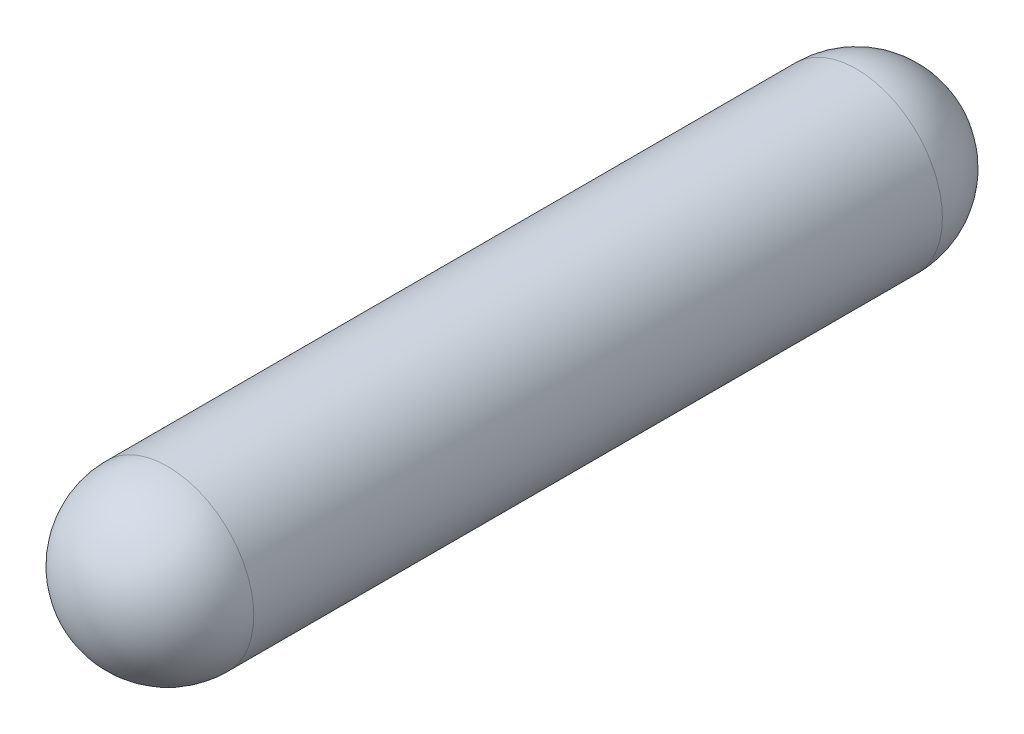
SolidWorks part; units mm, degrees
ref_plane "Front Plane" through (0, 0, 0) normal (0, 0, 1) x (1, 0, 0)
ref_plane "Top Plane" through (0, 0, 0) normal (0, 1, 0) x (1, 0, 0)
ref_plane "Right Plane" through (0, 0, 0) normal (1, 0, 0) x (0, 0, -1)
sketch "Sketch10" plane through (0, 0, 0) normal (0, 1, 0) x (1, 0, 0)
  line L0 (0, 0) -> (0, 10000)
  line L1 (1000, 1000) -> (1000, 9000)
  arc A0 (0, 0) -> (1000, 1000) centre (0, 1000) ccw
  arc A1 (0, 10000) -> (1000, 9000) centre (0, 9000) cw
  point P8 (0, 0)
  dimension "D2" = 1000
  dimension "D1" = 10000
revolve "Revolve2" add sketch "Sketch10" angle 360 about L0
equation "\"length\" = 10"
equation "\"x_wingbox\"= 10"
equation "\"x_tail\"= 0.5"
equation "\"D1@Sketch10\"=\"length\""
